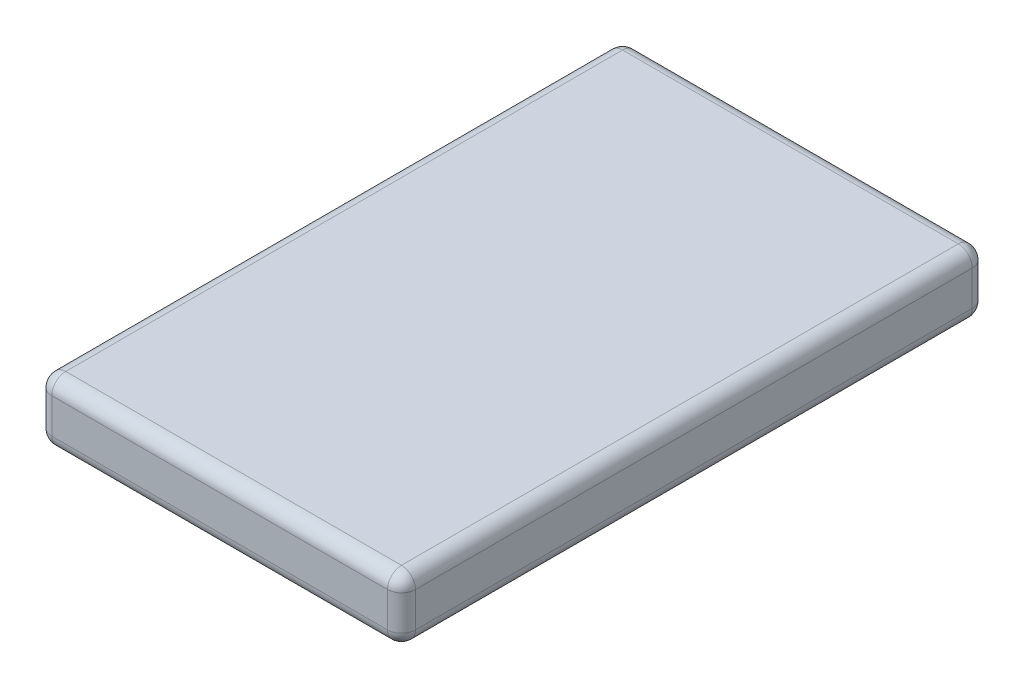
SolidWorks part; units mm, degrees
ref_plane "Front Plane" through (0, 0, 0) normal (0, 0, 1) x (1, 0, 0)
ref_plane "Top Plane" through (0, 0, 0) normal (0, 1, 0) x (1, 0, 0)
ref_plane "Right Plane" through (0, 0, 0) normal (1, 0, 0) x (0, 0, -1)
sketch "Sketch1" plane through (0, 0, 0) normal (0, 1, 0) x (1, 0, 0)
  line L1 (-16.51, -26.543) -> (16.51, -26.543)
  line L2 (-16.51, -26.543) -> (-16.51, 26.543)
  line L3 (-16.51, 26.543) -> (16.51, 26.543)
  line L4 (16.51, -26.543) -> (16.51, 26.543)
  line L5 (-16.51, -26.543) -> (16.51, 26.543) construction
  line L6 (-16.51, 26.543) -> (16.51, -26.543) construction
  point P0 (0, 0)
  dimension "D1" = 53.086
  dimension "D2" = 33.02
extrude "Boss-Extrude1" add sketch "Sketch1" along normal blind 5.715
fillet "Fillet1" radius 1.27 12 edges at (-16.51, 2.8575, -26.543) (16.51, 2.8575, -26.543) (-16.51, 2.8575, 26.543) (16.51, 2.8575, 26.543) (0, 0, -26.543) (-16.51, 0, 0) (0, 0, 26.543) (16.51, 0, 0) (0, 5.715, 26.543) (-16.51, 5.715, 0) (0, 5.715, -26.543) (16.51, 5.715, 0)
